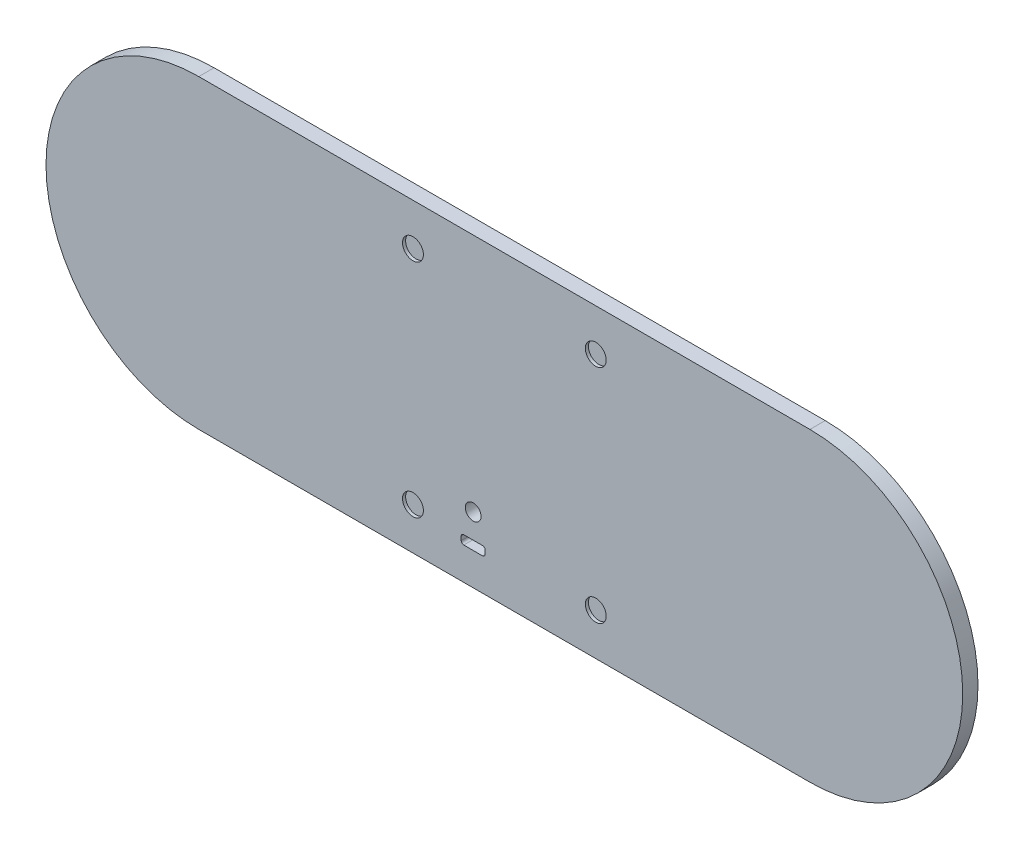
SolidWorks part; units mm, degrees
ref_plane "Plan de face" through (0, 0, 0) normal (0, 0, 1) x (1, 0, 0)
ref_plane "Plan de dessus" through (0, 0, 0) normal (0, 1, 0) x (1, 0, 0)
ref_plane "Plan de droite" through (0, 0, 0) normal (1, 0, 0) x (0, 0, -1)
sketch "Esquisse1" plane through (0, 0, 0) normal (0, 0, 1) x (1, 0, 0)
  line L0 (120, 0) -> (-120, 0) construction
  line L1 (120, -60) -> (-120, -60)
  line L2 (120, 60) -> (-120, 60)
  arc A0 (120, -60) -> (120, 60) centre (120, 0) ccw
  arc A1 (-120, 60) -> (-120, -60) centre (-120, 0) ccw
  point P2 (0, 0)
  dimension "D1" = 240
  dimension "D2" = 120
extrude "Boss.-Extru.1" add sketch "Esquisse1" along normal blind 6
sketch "Esquisse2" plane through (0, 0, 6) normal (0, 0, 1) x (1, 0, 0)
  circle A0 centre (-35.894, 43.5125) radius 4.1
  circle A1 centre (35.894, 43.5125) radius 4.1
  circle A2 centre (35.894, -43.5125) radius 4.1
  circle A3 centre (-35.894, -43.5125) radius 4.1
  dimension "D1" = 8.2
extrude "Enlèv. mat.-Extru.1" cut sketch "Esquisse2" against normal blind 1.22
sketch "Esquisse3" plane through (0, 0, 0) normal (0, 0, -1) x (-1, 0, 0)
  circle A0 centre (12.25, -34.19) radius 3.1
  dimension "D1" = 6.2
extrude "Enlèv. mat.-Extru.2" cut sketch "Esquisse3" against normal up to next
sketch "Esquisse5" plane through (0, 0, 6) normal (0, 0, 1) x (1, 0, 0)
  line L1 (-7.55, -47.29) -> (-16.95, -47.29)
  line L2 (-7.55, -47.29) -> (-7.55, -43.79)
  line L3 (-7.55, -43.79) -> (-16.95, -43.79)
  line L4 (-16.95, -47.29) -> (-16.95, -43.79)
  dimension "D1" = 9.4
  dimension "D2" = 3.5
extrude "Enlèv. mat.-Extru.3" cut sketch "Esquisse5" against normal up to next
fillet "Congé1" radius 1 4 edges at (-16.95, -47.29, 3) (-7.55, -47.29, 3) (-7.55, -43.79, 3) (-16.95, -43.79, 3)
